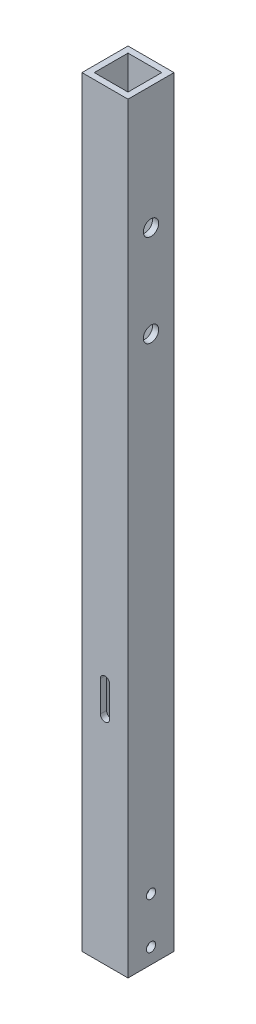
SolidWorks part; units mm, degrees
material "6061 合金"
ref_plane "前视基准面" through (0, 0, 0) normal (0, 0, 1) x (1, 0, 0)
ref_plane "上视基准面" through (0, 0, 0) normal (0, 1, 0) x (1, 0, 0)
ref_plane "右视基准面" through (0, 0, 0) normal (1, 0, 0) x (0, 0, -1)
sketch "草图1" plane through (0, 0, 0) normal (0, 1, 0) x (1, 0, 0)
  line L1 (-7.5, -7.5) -> (7.5, -7.5)
  line L2 (-7.5, -7.5) -> (-7.5, 7.5)
  line L3 (-7.5, 7.5) -> (7.5, 7.5)
  line L4 (7.5, -7.5) -> (7.5, 7.5)
  line L5 (-7.5, -7.5) -> (7.5, 7.5) construction
  line L6 (-7.5, 7.5) -> (7.5, -7.5) construction
  point P0 (0, 0)
extrude "凸台-拉伸1" add sketch "草图1" along normal blind 248
sketch "草图3" plane through (7.5, 0, 0) normal (1, 0, 0) x (0, 0, -1)
  line L0 (-7.5, 0) -> (7.5, 0) construction
  line L1 (7.5, 248) -> (7.5, 0) construction
  circle A0 centre (0, 5) radius 1.5
  circle A1 centre (0, 20) radius 1.5
  dimension "D1" = 5
  dimension "D2" = 20
  dimension "D3" = 3
  dimension "D4" = 3
  dimension "D5" = 7.5
  dimension "D6" = 7.5
extrude "切除-拉伸2" cut sketch "草图3" against normal blind 15
sketch "草图4" plane through (0, 0, 7.5) normal (0, 0, 1) x (1, 0, 0)
  line L0 (0, 70) -> (0, 80) construction
  line L1 (-7.5, 0) -> (7.5, 0) construction
  line L2 (-1.5, 70) -> (-1.5, 80)
  line L3 (1.5, 70) -> (1.5, 80)
  arc A0 (-1.5, 70) -> (1.5, 70) centre (0, 70) ccw
  arc A1 (1.5, 80) -> (-1.5, 80) centre (0, 80) ccw
  point P5 (0, 75)
  dimension "D3" = 1.5
  dimension "D1" = 75
  dimension "D2" = 5
extrude "切除-拉伸3" cut sketch "草图4" against normal blind 15
sketch "草图5" plane through (0, 248, 0) normal (0, 1, 0) x (1, 0, 0)
  line L1 (-5.5, 5.5) -> (5.5, 5.5)
  line L2 (-5.5, 5.5) -> (-5.5, -5.5)
  line L3 (-5.5, -5.5) -> (5.5, -5.5)
  line L4 (5.5, 5.5) -> (5.5, -5.5)
  line L5 (-5.5, 5.5) -> (5.5, -5.5) construction
  line L6 (-5.5, -5.5) -> (5.5, 5.5) construction
  point P0 (0, 0)
extrude "切除-拉伸4" cut sketch "草图5" against normal blind 248
sketch "草图6" plane through (-7.5, 0, 0) normal (-1, 0, 0) x (0, 0, 1)
  line L0 (-7.5, 248) -> (7.5, 248) construction
  circle A0 centre (0, 208) radius 2.5
  circle A1 centre (0, 178) radius 2.5
  dimension "D1" = 5
  dimension "D2" = 5
  dimension "D3" = 30
  dimension "D4" = 40
extrude "切除-拉伸5" cut sketch "草图6" against normal blind 15
